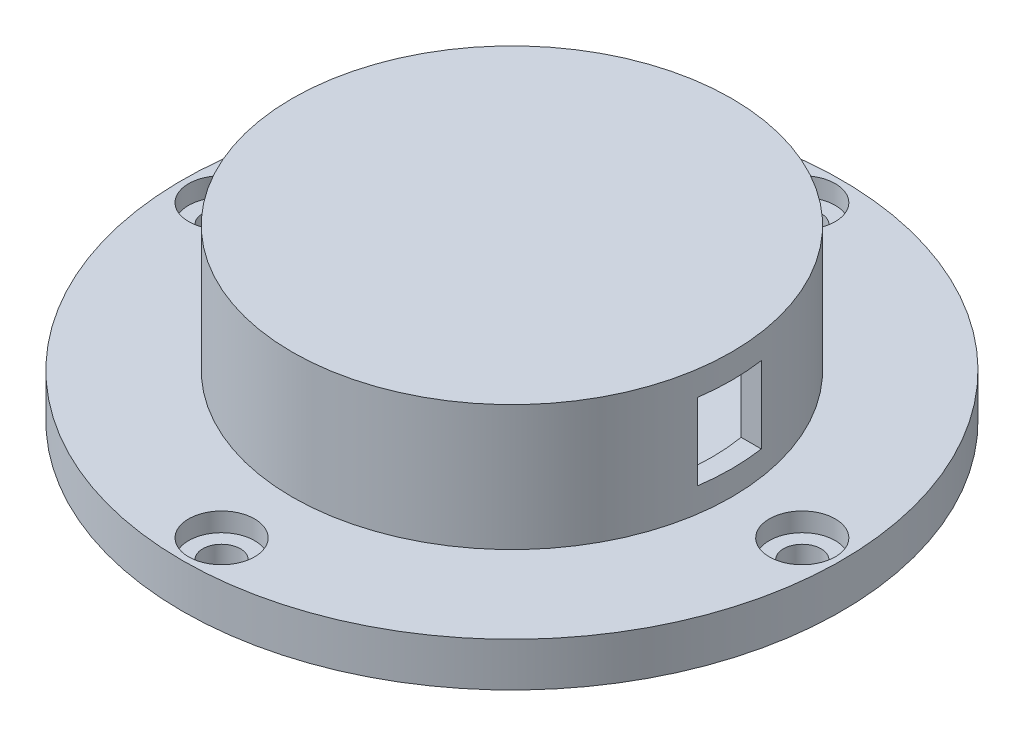
SolidWorks part; units mm, degrees
ref_plane "Front Plane" through (0, 0, 0) normal (0, 0, 1) x (1, 0, 0)
ref_plane "Top Plane" through (0, 0, 0) normal (0, 1, 0) x (1, 0, 0)
ref_plane "Right Plane" through (0, 0, 0) normal (1, 0, 0) x (0, 0, -1)
sketch "Sketch1" plane through (0, 0, 0) normal (0, 1, 0) x (1, 0, 0)
  circle A0 centre (0, 0) radius 52.5
  point P0 (0, 0)
  dimension "D1" = 105
extrude "Boss-Extrude1" add sketch "Sketch1" along normal blind 7
sketch "Sketch2" plane through (0, 7, 0) normal (0, 1, 0) x (1, 0, 0)
  circle A0 centre (0, 0) radius 35
  circle A1 centre (0, 0) radius 31.83
  point P0 (0, 0)
  dimension "D1" = 70
  dimension "D2" = 63.66
extrude "Boss-Extrude3" add sketch "Sketch2" along normal blind 20
sketch "Sketch3" plane through (0, 7, 0) normal (0, 1, 0) x (1, 0, 0)
  line L0 (0, 0) -> (52.5, 0) construction
  line L1 (52.5, 0) -> (-52.5, 0) construction
  line L2 (0, 0) -> (0, -52.5) construction
  line L3 (0, -52.5) -> (0, 52.5) construction
  line L4 (0, 52.5) -> (0, 46.25)
  circle A0 centre (0, 0) radius 52.5 construction
  circle A1 centre (0, 46.25) radius 3
  circle A2 centre (46.25, 0) radius 3
  circle A3 centre (0, -46.25) radius 3
  circle A4 centre (-46.25, 0) radius 3
  circle A5 centre (-46.25, 0) radius 5.025
  circle A6 centre (0, 46.25) radius 5.025
  circle A7 centre (46.25, 0) radius 5.025
  circle A8 centre (0, -46.25) radius 5.025
  dimension "D2" = 4
  dimension "D3" = 4
  dimension "D1" = 6.25
extrude "Cut-Extrude1" cut sketch "Sketch3" against normal blind 20 contours A1 | A4 | A3 | A2
sketch "Sketch4" plane through (0, 7, 0) normal (0, 1, 0) x (1, 0, 0)
  circle A0 centre (0, 46.25) radius 5.25
  circle A1 centre (46.25, 0) radius 5.25
  circle A2 centre (0, -46.25) radius 5.25
  circle A3 centre (-46.25, 0) radius 5.25
  point P0 (0, 46.25)
  dimension "D1" = 4
extrude "Cut-Extrude2" cut sketch "Sketch4" against normal blind 3
ref_plane "Plane1" through (60, 0, 0) normal (1, 0, 0) x (0, 0, -1)
sketch "Sketch5" plane through (60, 0, 0) normal (1, 0, 0) x (0, 0, -1)
  line L0 (0, 27) -> (0, 7)
  line L2 (35, 27) -> (-35, 27) construction
  line L3 (52.5, 7) -> (-52.5, 7) construction
  line L5 (-5.1, 23.1) -> (5.1, 23.1)
  line L6 (-5.1, 23.1) -> (-5.1, 10.9)
  line L7 (-5.1, 10.9) -> (5.1, 10.9)
  line L8 (5.1, 23.1) -> (5.1, 10.9)
  line L9 (-5.1, 23.1) -> (5.1, 10.9) construction
  line L10 (-5.1, 10.9) -> (5.1, 23.1) construction
  point P7 (0, 17)
  dimension "D1" = 10.2
  dimension "D2" = 12.2
extrude "Cut-Extrude3" cut sketch "Sketch5" against normal blind 120 contours L6 L7 L8 L5
ref_plane "Plane2" through (0, 27, 0) normal (0, 1, 0) x (1, 0, 0)
sketch "Sketch6" plane through (0, 27, 0) normal (0, 1, 0) x (1, 0, 0)
  circle A0 centre (0, 0) radius 31.83
extrude "Boss-Extrude4" add sketch "Sketch6" against normal blind 3
